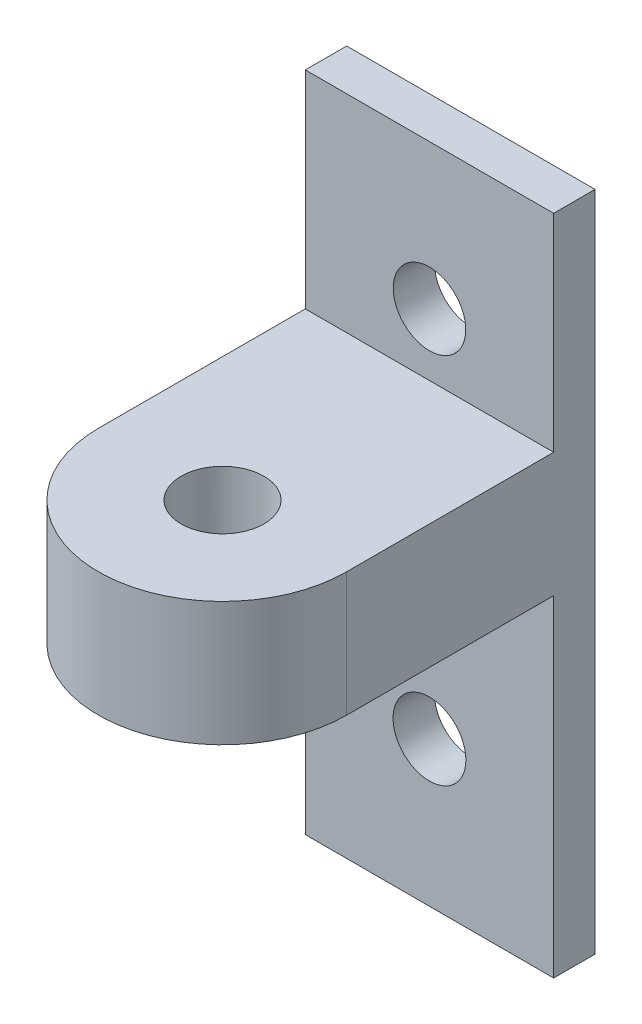
SolidWorks part; units mm, degrees
ref_plane "Front" through (0, 0, 0) normal (0, 0, 1) x (1, 0, 0)
ref_plane "Top" through (0, 0, 0) normal (0, 1, 0) x (1, 0, 0)
ref_plane "Right" through (0, 0, 0) normal (1, 0, 0) x (0, 0, -1)
sketch "Sketch1" plane through (0, 0, 0) normal (0, 0, 1) x (1, 0, 0)
  line L1 (-19.05, -50.8) -> (19.05, -50.8)
  line L2 (-19.05, -50.8) -> (-19.05, 50.8)
  line L3 (-19.05, 50.8) -> (19.05, 50.8)
  line L4 (19.05, -50.8) -> (19.05, 50.8)
  line L5 (-19.05, -50.8) -> (19.05, 50.8) construction
  line L6 (-19.05, 50.8) -> (19.05, -50.8) construction
  point P0 (0, 0)
  dimension "D1" = 38.1
  dimension "D2" = 101.6
extrude "Boss-Extrude1" add sketch "Sketch1" along normal blind 6.35
sketch "Sketch2" plane through (0, 0, 6.35) normal (0, 0, 1) x (1, 0, 0)
  line L0 (19.05, 50.8) -> (-19.05, 50.8) construction
  circle A0 centre (0, 28.575) radius 5.5626
  circle A1 centre (0, -28.575) radius 5.588
  dimension "D1" = 11.1252
  dimension "D2" = 11.176
  dimension "D3" = 22.225
  dimension "D4" = 57.15
extrude "Cut-Extrude1" cut sketch "Sketch2" against normal through all
sketch "Sketch3" plane through (0, 0, 6.35) normal (0, 0, 1) x (1, 0, 0)
  line L0 (19.05, -50.8) -> (19.05, 50.8) construction
  line L5 (-19.05, 0) -> (19.05, 0)
  line L6 (-19.05, 0) -> (-19.05, 19.05)
  line L7 (-19.05, 19.05) -> (19.05, 19.05)
  line L8 (19.05, 0) -> (19.05, 19.05)
  line L9 (-19.05, 0) -> (19.05, 19.05) construction
  line L10 (-19.05, 19.05) -> (19.05, 0) construction
  line L11 (-19.05, 0) -> (19.05, 0)
  point P0 (0, 9.525)
  point P11 (0, 0)
  line M11 (19.05, -50.8) -> (19.05, 50.8)
  line M13 (-19.05, 50.8) -> (-19.05, -50.8)
  dimension "D1" = 0
  dimension "D2" = 19.05
extrude "Boss-Extrude2" add sketch "Sketch3" along normal blind 31.75 contours L7 L5 M13 M11
sketch "Sketch4" plane through (0, 0, 0) normal (0, -1, 0) x (1, 0, 0)
  line L4 (-19.05, 6.35) -> (19.05, 6.35)
  line L5 (19.05, 6.35) -> (19.05, 38.1)
  line L6 (19.05, 38.1) -> (-19.05, 38.1)
  line L7 (-19.05, 38.1) -> (-19.05, 6.35)
  line L10 (19.05, 38.1) -> (-19.05, 38.1)
  arc A0 (19.05, 38.1) -> (-19.05, 38.1) centre (0, 38.1) ccw
  dimension "D1" = 0
extrude "Boss-Extrude3" add sketch "Sketch4" against normal up to vertex (19.05 mm away) up to point (-19.05, 19.05, 38.1)
sketch "Sketch5" plane through (0, 0, 0) normal (0, -1, 0) x (1, 0, 0)
  circle A0 centre (0, 38.1) radius 6.35
  dimension "D1" = 12.7
extrude "Cut-Extrude2" cut sketch "Sketch5" against normal through all
equation "\"hingmountinghole\"=0.438"
equation "\"D1@Sketch2\"=\"hingmountinghole\""
